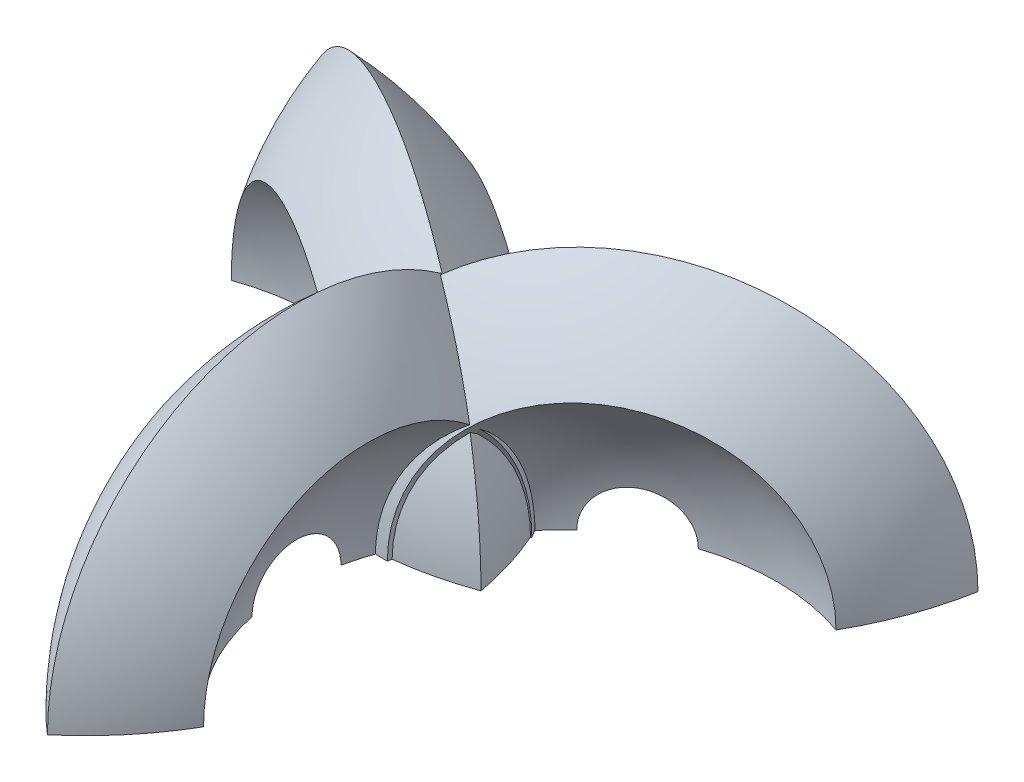
SolidWorks part; units mm, degrees
ref_plane "Front Plane" through (0, 0, 0) normal (0, 0, 1) x (1, 0, 0)
ref_plane "Top Plane" through (0, 0, 0) normal (0, 1, 0) x (1, 0, 0)
ref_plane "Right Plane" through (0, 0, 0) normal (1, 0, 0) x (0, 0, -1)
sketch "bottom sketch template" plane through (0, 0, 0) normal (0, 1, 0) x (1, 0, 0)
  line L0 (-177.6403, 0) -> (177.6403, 0) construction
  line L1 (0, 150.0743) -> (0, -150.0743) construction
  line L2 (-88.9, 150.0743) -> (88.9, 150.0743) construction
  line L3 (88.9, 150.0743) -> (177.6403, 0) construction
  line L4 (177.6403, 0) -> (82.296, -150.0743) construction
  line L5 (82.296, -150.0743) -> (-82.296, -150.0743) construction
  line L6 (-82.296, -150.0743) -> (-177.6403, 0) construction
  line L7 (-177.6403, 0) -> (-88.9, 150.0743) construction
  line L8 (129.9682, -75.0372) -> (0, 0) construction
  line L9 (0, 0) -> (-129.9682, -75.0372) construction
  line L10 (0, 0) -> (136.1081, -65.3728) construction
  line L11 (123.8607, -84.6505) -> (0, 0) construction
  line L12 (0, 0) -> (-124.6685, -85.1867) construction
  line L13 (-135.2398, -64.9412) -> (0, 0) construction
  line L14 (0, 0) -> (-11.4395, 150.5594) construction
  line L15 (11.3791, 149.5917) -> (0, 0) construction
  line L16 (136.1081, -65.3728) -> (11.3791, 149.5917) construction
  line L17 (-11.4395, 150.5594) -> (-135.2398, -64.9412) construction
  line L18 (-124.6685, -85.1867) -> (123.8607, -84.6505) construction
  point P4 (0, 0)
  point P5 (0, 0)
  point P10 (0, 150.0743)
  point P11 (0, -150.0743)
  dimension "D1" = 177.8
  dimension "D2" = 164.592
  dimension "D3" = 30
  dimension "D4" = 4.345
  dimension "D5" = 4.35
ref_plane "4-5 leg planes" through (0, 0, 84.6505) normal (0, 0, 1) x (1, 0, 0)
ref_plane "1-6 leg planes" through (73.449, 0, -42.6173) normal (0.8649, 0, -0.5019) x (-0.5019, 0, -0.8649)
ref_plane "2-3 leg planes" through (-73.6321, 0, -42.3) normal (-0.8671, 0, -0.4981) x (-0.4981, 0, 0.8671)
ref_plane "3-4 leg plane" through (-126.5583, 0, 80.4043) normal (0.8441, 0, -0.5362) x (-0.5362, 0, -0.8441)
ref_plane "1-2 leg plane" through (0, 0, -150.0743) normal (0, 0, -1) x (-1, 0, 0)
ref_plane "5-6 leg plane" through (126.5583, 0, 80.4043) normal (-0.8441, 0, -0.5362) x (-0.5362, 0, 0.8441)
sketch "Sketch4" plane through (0, 0, 84.6505) normal (0, 0, 1) x (1, 0, 0)
  line L0 (-124.6685, 0) -> (123.8607, 0) construction
  line L1 (-124.6685, 0) -> (123.8607, 0) construction
  arc A0 (-42.3343, -96.6958) -> (-0.4039, -26.2166) centre (-124.6685, 0) ccw construction
  arc A1 (-0.4039, -146.7281) -> (41.5264, -96.6958) centre (-124.6685, 0) ccw construction
  arc A2 (41.5264, 96.6958) -> (-0.4039, 26.2166) centre (123.8607, 0) ccw
  arc A3 (-0.4039, 146.7281) -> (-42.3343, 96.6958) centre (123.8607, 0) ccw
  arc A4 (-42.3343, -96.6958) -> (-0.4039, -146.7281) centre (123.8607, 0) ccw construction
  arc A5 (41.5264, 96.6958) -> (-0.4039, 146.7281) centre (-124.6685, 0) ccw
  arc A6 (-0.4039, -26.2166) -> (41.5264, -96.6958) centre (123.8607, 0) ccw construction
  arc A7 (-0.4039, 26.2166) -> (-42.3343, 96.6958) centre (-124.6685, 0) ccw
  dimension "D1" = 254
  dimension "D2" = 384.556
revolve "4-5 leg revolve" add sketch "Sketch4" angle 180 mid plane about L1
sketch "Sketch5" plane through (73.449, 0, -42.6173) normal (0.8649, 0, -0.5019) x (-0.5019, 0, -0.8649)
  line L0 (-124.852, 0) -> (123.6778, 0) construction
  line L1 (-124.852, 0) -> (123.6778, 0) construction
  arc A0 (-42.5174, -96.6954) -> (-0.5871, -26.2152) centre (-124.852, 0) ccw construction
  arc A1 (-0.5871, -146.7279) -> (41.3431, -96.6954) centre (-124.852, 0) ccw construction
  arc A2 (41.3431, 96.6954) -> (-0.5871, 26.2152) centre (123.6778, 0) ccw
  arc A3 (-0.5871, 146.7279) -> (-42.5174, 96.6954) centre (123.6778, 0) ccw
  arc A4 (-42.5174, -96.6954) -> (-0.5871, -146.7279) centre (123.6778, 0) ccw construction
  arc A5 (41.3431, 96.6954) -> (-0.5871, 146.7279) centre (-124.852, 0) ccw
  arc A6 (-0.5871, 26.2152) -> (-42.5174, 96.6954) centre (-124.852, 0) ccw
  arc A7 (-0.5871, -26.2152) -> (41.3431, -96.6954) centre (123.6778, 0) ccw construction
  dimension "D1" = 254
  dimension "D2" = 384.556
revolve "1-6 leg revolve" add sketch "Sketch5" angle 180 mid plane about L1
sketch "Sketch6" plane through (-73.6321, 0, -42.3) normal (-0.8671, 0, -0.4981) x (-0.4981, 0, 0.8671)
  line L0 (-124.852, 0) -> (123.6778, 0) construction
  line L1 (-124.852, 0) -> (123.6778, 0) construction
  arc A0 (-42.5174, -96.6954) -> (-0.5871, -26.2152) centre (-124.852, 0) ccw construction
  arc A1 (41.3431, 96.6954) -> (-0.5871, 26.2152) centre (123.6778, 0) ccw
  arc A2 (-0.5871, 146.7279) -> (-42.5174, 96.6954) centre (123.6778, 0) ccw
  arc A3 (-0.5871, -146.7279) -> (41.3431, -96.6954) centre (-124.852, 0) ccw construction
  arc A4 (-42.5174, -96.6954) -> (-0.5871, -146.7279) centre (123.6778, 0) ccw construction
  arc A5 (41.3431, 96.6954) -> (-0.5871, 146.7279) centre (-124.852, 0) ccw
  arc A6 (-0.5871, 26.2152) -> (-42.5174, 96.6954) centre (-124.852, 0) ccw
  arc A7 (-0.5871, -26.2152) -> (41.3431, -96.6954) centre (123.6778, 0) ccw construction
  dimension "D1" = 254
  dimension "D2" = 384.556
revolve "2-3 leg revolve" add sketch "Sketch6" angle 180 mid plane about L1
sketch "Sketch7" plane through (-126.5583, 0, 80.4043) normal (0.8441, 0, -0.5362) x (-0.5362, 0, -0.8441)
  line L0 (-82.5413, 0) -> (95.2587, 0) construction
  line L1 (-82.5413, 0) -> (95.2587, 0) construction
  circle A0 centre (17.7072, 0) radius 127
  circle A1 centre (17.7072, 0) radius 192.278
  circle A2 centre (-5.05, 0) radius 127
  circle A3 centre (-5.05, 0) radius 192.278
  point P9 (0, 0)
  dimension "D1" = 254
  dimension "D2" = 384.556
